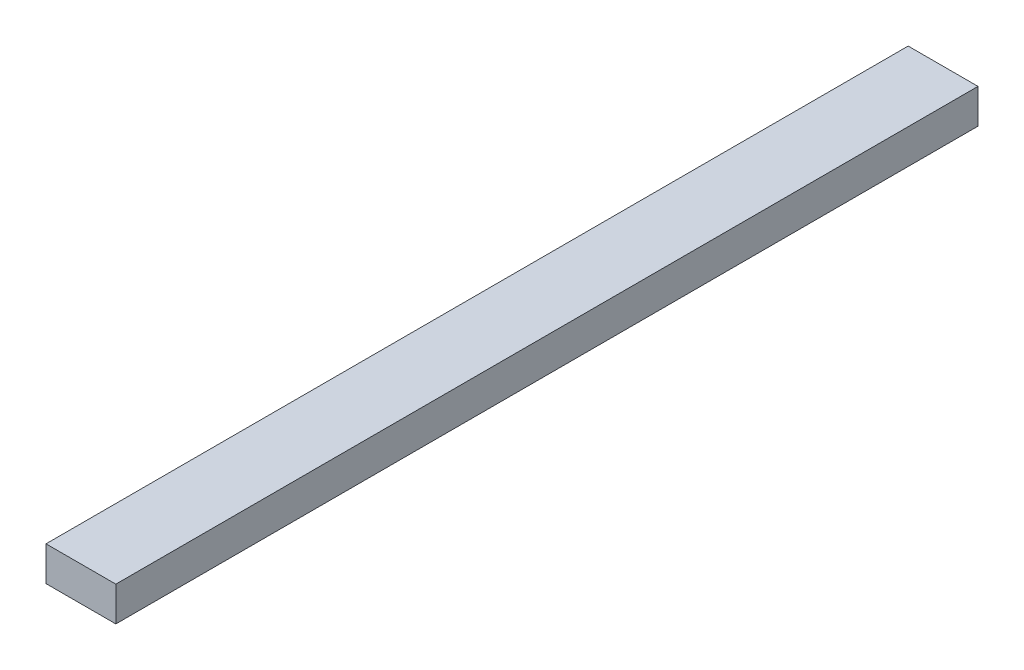
SolidWorks part; units mm, degrees
ref_plane "Front Plane" through (0, 0, 0) normal (0, 0, 1) x (1, 0, 0)
ref_plane "Top Plane" through (0, 0, 0) normal (0, 1, 0) x (1, 0, 0)
ref_plane "Right Plane" through (0, 0, 0) normal (1, 0, 0) x (0, 0, -1)
sketch "Sketch1" plane through (0, 0, 0) normal (0, 0, 1) x (1, 0, 0)
  line L1 (-6.075, -3) -> (6.075, -3)
  line L2 (-6.075, -3) -> (-6.075, 3)
  line L3 (-6.075, 3) -> (6.075, 3)
  line L4 (6.075, -3) -> (6.075, 3)
  line L5 (-6.075, -3) -> (6.075, 3) construction
  line L6 (-6.075, 3) -> (6.075, -3) construction
  point P0 (0, 0)
  dimension "D1" = 6
  dimension "D2" = 12.15
extrude "Boss-Extrude1" add sketch "Sketch1" along normal blind 150
